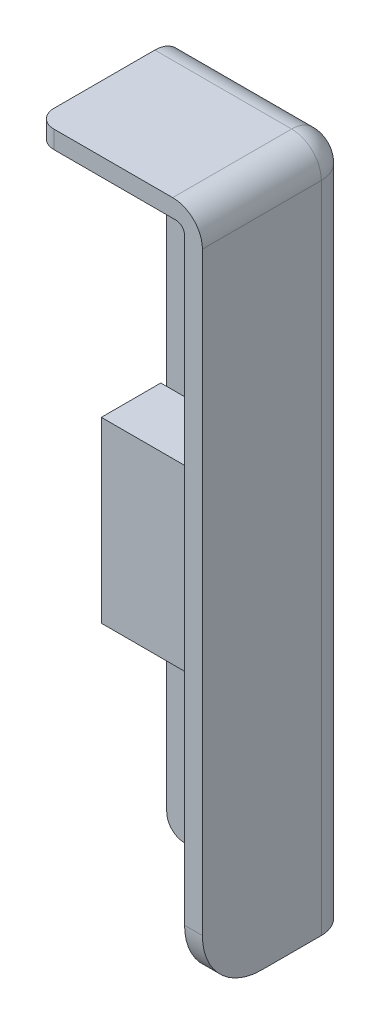
SolidWorks part; units mm, degrees
material "ABS"
ref_plane "Front" through (0, 0, 0) normal (0, 0, 1) x (1, 0, 0)
ref_plane "Top" through (0, 0, 0) normal (0, 1, 0) x (1, 0, 0)
ref_plane "Right" through (0, 0, 0) normal (1, 0, 0) x (0, 0, -1)
sketch "Sketch1" plane through (0, 0, 0) normal (1, 0, 0) x (0, 0, -1)
  line L1 (-12.5, 57.5) -> (12.5, 57.5)
  line L2 (-12.5, 57.5) -> (-12.5, -57.5)
  line L3 (-12.5, -57.5) -> (12.5, -57.5)
  line L4 (12.5, 57.5) -> (12.5, -57.5)
  line L5 (-12.5, 57.5) -> (12.5, -57.5) construction
  line L6 (-12.5, -57.5) -> (12.5, 57.5) construction
  point P0 (0, 0)
  dimension "D1" = 25
  dimension "D2" = 115
extrude "Boss-Extrude1" add sketch "Sketch1" along normal mid plane 28
sketch "Sketch3" plane through (-14, 0, 0) normal (1, 0, 0) x (0, 0, -1)
  line L1 (-12.5, -57.5) -> (9.5, -57.5)
  line L2 (-12.5, -57.5) -> (-12.5, 54.5)
  line L3 (-12.5, 54.5) -> (9.5, 54.5)
  line L4 (9.5, -57.5) -> (9.5, 54.5)
  dimension "D1" = 22
  dimension "D2" = 112
extrude "Cut-Extrude1" cut sketch "Sketch3" along normal offset from surface (25 mm away) 3 up to face at (14, 0, 0)
sketch "Sketch4" plane through (11, 0, 0) normal (-1, 0, 0) x (0, 0, 1)
  line L0 (12.5, -1.5) -> (-9.5, -1.5) construction
  line L1 (12.5, 54.5) -> (12.5, -57.5) construction
  line L2 (-9.5, -57.5) -> (-9.5, 54.5) construction
  line L4 (-3.5, 13.5) -> (6.5, 13.5)
  line L5 (-3.5, 13.5) -> (-3.5, -16.5)
  line L6 (-3.5, -16.5) -> (6.5, -16.5)
  line L7 (6.5, 13.5) -> (6.5, -16.5)
  line L8 (-3.5, 13.5) -> (6.5, -16.5) construction
  line L9 (-3.5, -16.5) -> (6.5, 13.5) construction
  point P6 (1.5, -1.5)
  dimension "D1" = 30
  dimension "D2" = 10
extrude "Boss-Extrude2" add sketch "Sketch4" along normal blind 20
hole_wizard "#2 Clearance Hole1" positions "Sketch5" profile "Sketch6" hole size "#2" standard "ANSI Inch"
sketch "Sketch5" plane through (-9, 0, 0) normal (-1, 0, 0) x (0, 0, 1)
  line L0 (1.5, 13.5) -> (1.5, -16.5) construction
  line L1 (6.5, 13.5) -> (-3.5, 13.5) construction
  line L2 (-3.5, -16.5) -> (6.5, -16.5) construction
  line L4 (-3.5, -1.5) -> (6.5, -1.5) construction
  line L5 (-3.5, 13.5) -> (-3.5, -16.5) construction
  line L6 (6.5, -16.5) -> (6.5, 13.5) construction
  point P0 (1.5, 8.5)
  point P2 (1.5, -11.5)
  dimension "D1" = 10
  dimension "D2" = 10
sketch "Sketch6" plane through (-9, 8.5, 1.5) normal (0, 1, 0) x (0, 0, 1)
  line L0 (0, 0) -> (0, 7.0292)
  line L1 (0, 7.0292) -> (1.1303, 6.35)
  line L2 (1.1303, 6.35) -> (1.1303, 0)
  line L5 (1.1303, 0) -> (0, 0)
  line L10 (0, 7.0292) -> (-1.1303, 6.35) construction
  line L11 (0, -6.35) -> (0, 107.95) construction
  dimension "Hole Dia." = 2.2606
  dimension "Hole Depth" = 6.35
  dimension "Drill Angle" = 118
fillet "Fillet1" radius 1.5 3 edges at (11, -1.5, -9.5) (-1.5, 54.5, -9.5) (11, 54.5, 1.5)
fillet "Fillet3" radius 5 3 edges at (0, 57.5, -12.5) (14, 57.5, 0) (14, 0, -12.5)
fillet "Fillet4" radius 10 1 edges at (12.5, -57.5, 12.5)
fillet "Fillet5" radius 3 2 edges at (-14, -57.5, -11) (-14, 56, 12.5)
fillet "Fillet6" radius 3 4 edges at (11, 13.5, 1.5) (11, -1.5, -3.5) (11, -16.5, 1.5) (11, -1.5, 6.5)
sketch "Sketch7" plane through (14, 0, 0) normal (1, 0, 0) x (0, 0, -1)
  circle A0 centre (-1.5, -43) radius 3.5 construction
  arc A1 (-3.2063, -46.0559) -> (-3.7669, -40.3333) centre (-1.5, -43) ccw construction
  circle A2 centre (-1.5, -43) radius 2.5
  dimension "D1" = 1
extrude "Boss-Extrude3" add sketch "Sketch7" against normal blind 8
fillet "Fillet7" radius 1 2 edges at (11, -43, -1) (6, -43, -1)
move or copy body "Body-Move/Copy1" [suppressed] bodies to move or copy 105
